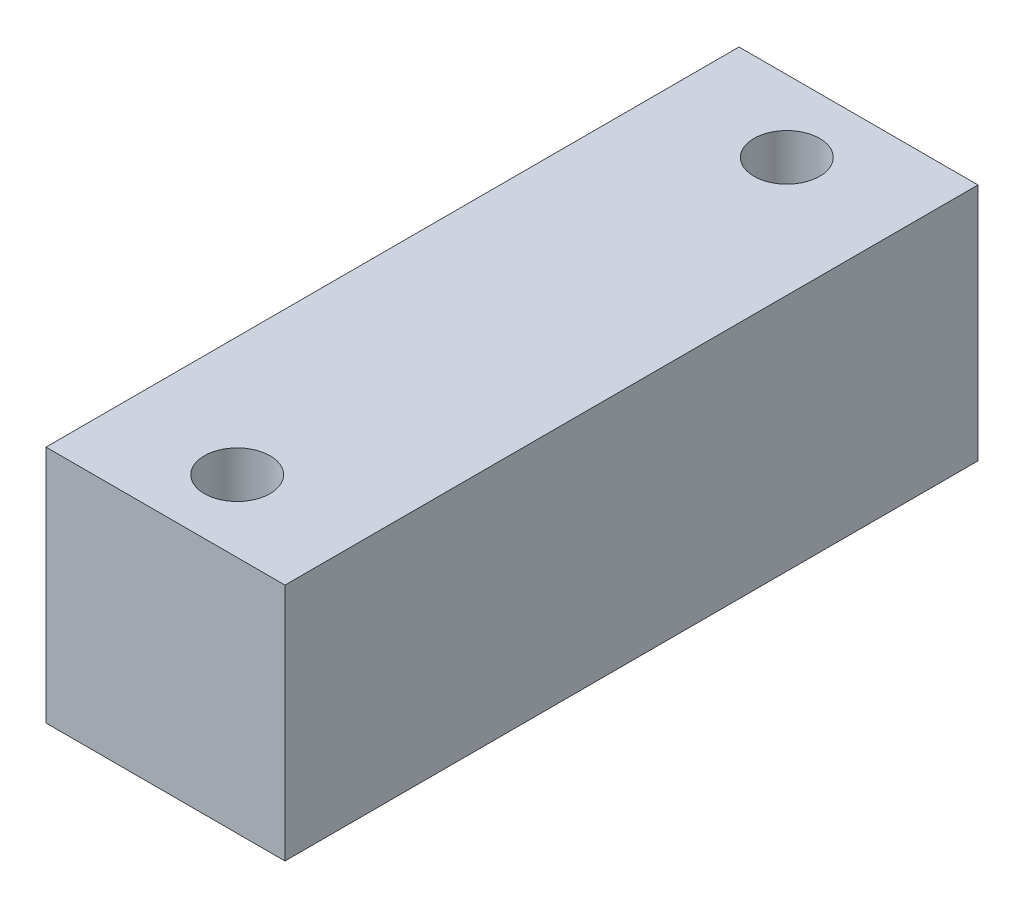
SolidWorks part; units mm, degrees
ref_plane "前视基准面" through (0, 0, 0) normal (0, 0, 1) x (1, 0, 0)
ref_plane "上视基准面" through (0, 0, 0) normal (0, 1, 0) x (1, 0, 0)
ref_plane "右视基准面" through (0, 0, 0) normal (1, 0, 0) x (0, 0, -1)
other "Configuration Table"
sketch "草图1" plane through (0, 0, 0) normal (0, 0, 1) x (1, 0, 0)
  line L1 (-10, -10) -> (10, -10)
  line L2 (-10, -10) -> (-10, 10)
  line L3 (-10, 10) -> (10, 10)
  line L4 (10, -10) -> (10, 10)
  line L5 (-10, -10) -> (10, 10) construction
  line L6 (-10, 10) -> (10, -10) construction
  line L11 (-8, -8) -> (8, 8) construction
  line L12 (-8, 8) -> (8, -8) construction
  point P0 (0, 0)
  point P6 (0, 0)
  dimension "D1" = 20
  dimension "D2" = 20
extrude "凸台-拉伸1" add sketch "草图1" along normal blind 58
sketch "草图2" plane through (0, 10, 0) normal (0, 1, 0) x (1, 0, 0)
  line L0 (0, 0) -> (0, -58) construction
  line L1 (10, 0) -> (-10, 0) construction
  line L2 (10, -58) -> (-10, -58) construction
  line L3 (10, -29) -> (-10, -29) construction
  line L4 (10, -58) -> (10, 0) construction
  line L5 (-10, -58) -> (-10, 0) construction
  circle A0 centre (0, -6) radius 2.75
  circle A1 centre (0, -52) radius 2.75
  dimension "D1" = 5.5
  dimension "D2" = 23
extrude "切除-拉伸1" cut sketch "草图2" against normal through all
